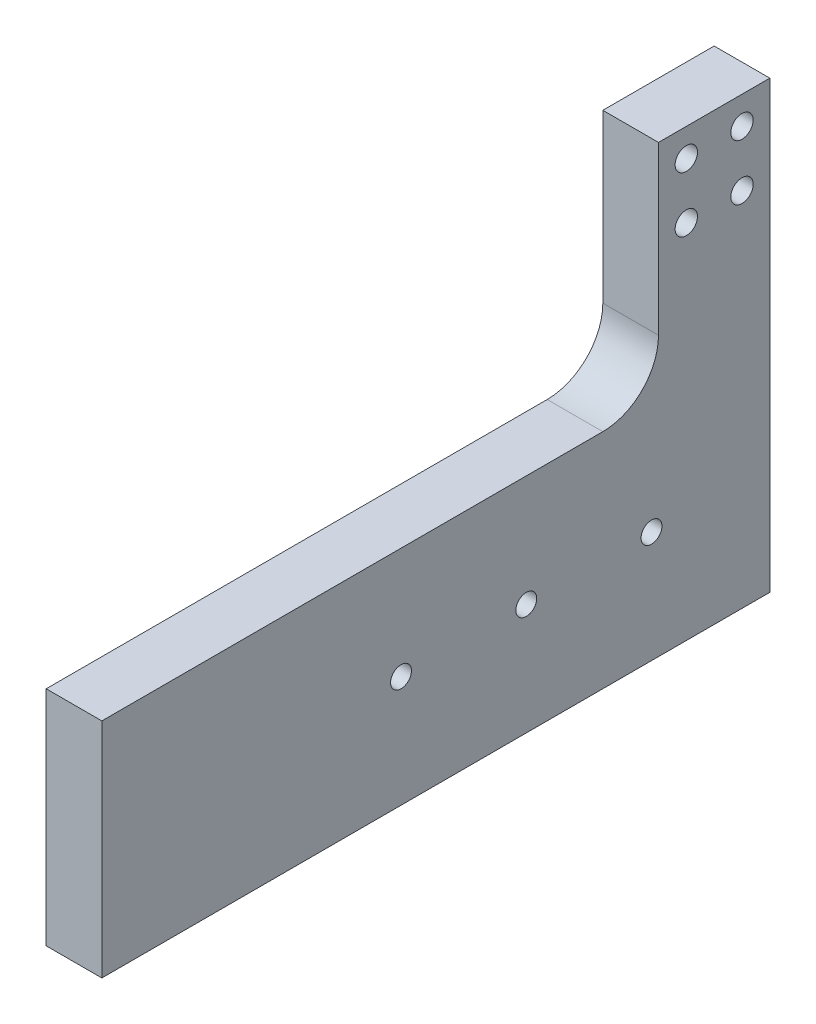
SolidWorks part; units mm, degrees
material "6061-T6 (SS)"
ref_plane "Front Plane" through (0, 0, 0) normal (0, 0, 1) x (1, 0, 0)
ref_plane "Top Plane" through (0, 0, 0) normal (0, 1, 0) x (1, 0, 0)
ref_plane "Right Plane" through (0, 0, 0) normal (1, 0, 0) x (0, 0, -1)
sketch "Sketch1" plane through (0, 0, 0) normal (1, 0, 0) x (0, 0, -1)
  line L0 (0, 0) -> (0, 101.6)
  line L1 (0, 101.6) -> (-25.4, 101.6)
  line L2 (-25.4, 101.6) -> (-25.4, 50.8)
  line L3 (-25.4, 50.8) -> (-152.4, 50.8)
  line L4 (-152.4, 50.8) -> (-152.4, 0)
  line L5 (-152.4, 0) -> (0, 0)
  line L6 (-26.9875, 25.4) -> (-84.1375, 25.4) construction
  circle A0 centre (-84.1375, 25.4) radius 2.3813
  circle A1 centre (-55.5625, 25.4) radius 2.3813
  circle A2 centre (-26.9875, 25.4) radius 2.3813
  dimension "D5" = 4.7625
  dimension "D6" = 26.9875
  dimension "D7" = 55.5625
  dimension "D8" = 84.1375
  dimension "D1" = 101.6
  dimension "D2" = 152.4
  dimension "D3" = 50.8
  dimension "D4" = 25.4
  dimension "D9" = 25.4
extrude "Boss-Extrude1" add sketch "Sketch1" along normal blind 12.7
hole_wizard "#10 Clearance Hole1" positions "Sketch2" profile "Sketch3" hole size "#10" standard "ANSI Inch" end condition through all
sketch "Sketch2" plane through (12.7, 0, 0) normal (1, 0, 0) x (0, 0, -1)
  line L0 (-25.4, 101.6) -> (-25.4, 50.8) construction
  line L1 (0, 0) -> (0, 101.6) construction
  point P0 (-19.05, 95.25)
  point P2 (-6.35, 95.25)
  point P4 (-6.35, 82.55)
  point P6 (-19.05, 82.55)
  dimension "D1" = 6.35
  dimension "D2" = 6.35
  dimension "D3" = 6.35
  dimension "D4" = 6.35
  dimension "D5" = 12.7
  dimension "D6" = 12.7
  dimension "D7" = 6.35
  dimension "D8" = 6.35
sketch "Sketch3" plane through (12.7, 95.25, 19.05) normal (0, 1, 0) x (0, 0, -1)
  line L0 (0, 0) -> (0, 12.7)
  line L1 (0, 12.7) -> (2.5527, 12.7)
  line L2 (2.5527, 12.7) -> (2.5527, 0)
  line L5 (2.5527, 0) -> (0, 0)
  line L11 (0, -6.35) -> (0, 107.95) construction
  dimension "Thru Hole Dia." = 5.1054
  dimension "Thru Hole Depth" = 12.7
ref_point "Point1"
ref_point "Point2"
ref_point "Point3"
fillet "Fillet1" radius 12.7 1 edges at (6.35, 50.8, 25.4)
